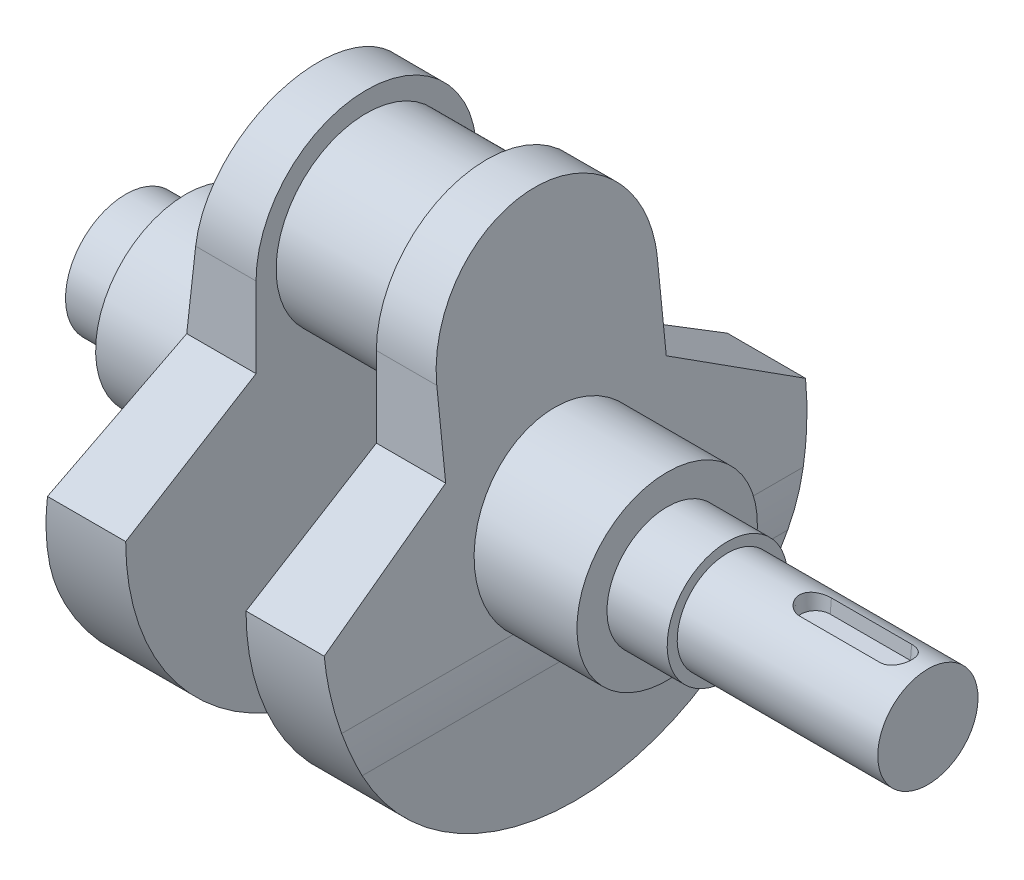
SolidWorks part; units mm, degrees
ref_plane "Front Plane" through (0, 0, 0) normal (0, 0, 1) x (1, 0, 0)
ref_plane "Top Plane" through (0, 0, 0) normal (0, 1, 0) x (1, 0, 0)
ref_plane "Right Plane" through (0, 0, 0) normal (1, 0, 0) x (0, 0, -1)
sketch "Sketch1" plane through (0, 0, 0) normal (1, 0, 0) x (0, 0, -1)
  circle A0 centre (0, 0) radius 22.5
  dimension "D1" = 45
extrude "Boss-Extrude1" add sketch "Sketch1" along normal blind 15
sketch "Sketch2" plane through (15, 0, 0) normal (1, 0, 0) x (0, 0, -1)
  line L0 (-27.5, 0) -> (-27.5, -20)
  line L1 (-27.5, -20) -> (-60, -40)
  line L2 (0, 0) -> (0, -39.4751) construction
  line L3 (27.5, 0) -> (27.5, -20)
  line L4 (27.5, -20) -> (60, -40)
  arc A0 (27.5, 0) -> (-27.5, 0) centre (0, 0) ccw
  arc A1 (-60, -40) -> (60, -40) centre (0, -40) ccw
  point P11 (0, 0)
  point P12 (0, 0)
  dimension "D1" = 120
  dimension "D3" = 55
  dimension "D2" = 40
  dimension "D4" = 20
extrude "Boss-Extrude2" add sketch "Sketch2" along normal blind 22
sketch "Sketch4" plane through (0, 0, 0) normal (0, 0, 1) x (1, 0, 0)
  line L0 (27, 27.5) -> (37, 27.5)
  line L1 (37, 27.5) -> (15, 27.5) construction
  line L2 (37, 27.5) -> (37, -62.5)
  line L3 (37, -100) -> (37, -40) construction
  line L4 (27, 27.5) -> (37, -62.5)
  dimension "D1" = 10
  dimension "D2" = 90
extrude "Cut-Extrude1" cut sketch "Sketch4" against normal through all both and the other way through all
fillet "Fillet1" radius 100 1 edges at (37, -62.5, 0)
sketch "Sketch5" plane through (0, 0, 0) normal (0, 0, 1) x (1, 0, 0)
  line L0 (37, -100) -> (37, 0) construction
  line L1 (37, -100) -> (37, -68.0385) construction
  line L2 (37, 0) -> (0, 0) construction
  line L3 (32, -17.5) -> (60, -17.5)
  line L4 (60, -17.5) -> (60, -25)
  line L5 (60, -25) -> (75, -25)
  line L6 (75, -25) -> (75, -27.5)
  line L7 (75, -27.5) -> (125, -27.5)
  line L8 (125, -27.5) -> (125, -40)
  line L9 (125, -40) -> (32, -40)
  line L10 (32, -40) -> (32, -17.5)
  line L11 (32, -40) -> (-10.0953, -40) construction
  line L12 (32.2778, -20) -> (30.0556, 0) construction
  point P8 (0, 0)
  dimension "D1" = 40
  dimension "D2" = 45
  dimension "D3" = 30
  dimension "D4" = 25
  dimension "D5" = 60
  dimension "D6" = 50
  dimension "D7" = 15
revolve "Revolve1" add sketch "Sketch5" angle 360 about L9
sketch "Sketch6" plane through (0, 0, 0) normal (0, 1, 0) x (1, 0, 0)
  line L0 (125, 0) -> (75, 0) construction
  line L1 (125, -12.5) -> (125, 12.5) construction
  line L2 (75, -12.5) -> (75, 12.5) construction
  line L3 (97, 0) -> (117, 0) construction
  line L4 (97, 4) -> (117, 4)
  line L5 (97, -4) -> (117, -4)
  arc A0 (97, 4) -> (97, -4) centre (97, 0) ccw
  arc A1 (117, -4) -> (117, 4) centre (117, 0) ccw
  point P5 (107, 0)
  dimension "D2" = 4
  dimension "D1" = 20
  dimension "D3" = 8
extrude "Cut-Extrude2" cut sketch "Sketch6" against normal blind 4 draft 5 from offset 27.5 offset against normal yes
mirror "Mirror1" about plane through (0, 0, 0) normal (1, 0, 0) of bodies 105
sketch "Sketch7" plane through (0, 0, 0) normal (0, 0, 1) x (1, 0, 0)
  line L0 (-75, -87.5642) -> (-75, 8.2918)
extrude "Cut-Extrude3" cut sketch "Sketch7" against normal through all and the other way through all
